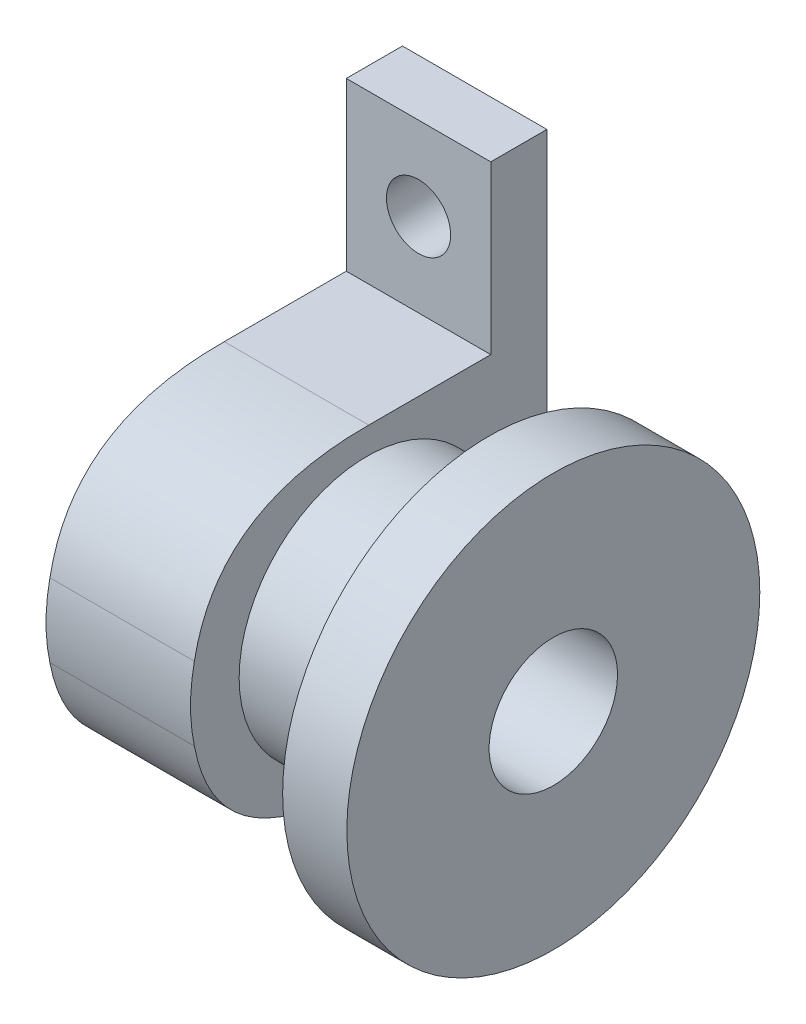
SolidWorks part; units mm, degrees
ref_plane "Front Plane" through (0, 0, 0) normal (1, 0, 0) x (0, 1, 0)
ref_plane "Top Plane" through (0, 0, 0) normal (0, 0, 1) x (0, 1, 0)
ref_plane "Right Plane" through (0, 0, 0) normal (0, 1, 0) x (-1, 0, 0)
sketch "Sketch1" plane through (0, 0, 0) normal (0, 0, 1) x (0, 1, 0)
  line L0 (-50, 0) -> (50, 0)
  line L1 (-50, 0) -> (-50, -22.5)
  line L2 (-50, -22.5) -> (50, -22.5)
  line L3 (50, -22.5) -> (50, 0)
  point P4 (0, 0)
  dimension "D1" = 100
  dimension "D2" = 22.5
extrude "Boss-Extrude1" add sketch "Sketch1" along normal blind 55.5
sketch "Sketch2" plane through (22.5, 0, 0) normal (1, 0, 0) x (0, 1, 0)
  line L0 (0, 0) -> (0, 0.5)
  line L1 (-24, 0) -> (-24, 55.5)
  line L2 (-50, 0) -> (50, 0) construction
  line L4 (-50, 55.5) -> (-50, 0) construction
  line L5 (50, 55.5) -> (50, 0) construction
  line L6 (19.6311, 8.742) -> (50, 8.742)
  line L8 (50, 55.5) -> (50, 14.5743)
  line L10 (-50, 55.5) -> (50, 55.5) construction
  line L12 (24, 0) -> (24, 55.5)
  line L13 (0, 0.5) -> (0, 55.5)
  line L14 (-24, 8.742) -> (-19.6311, 8.742)
  line L15 (-24, 8.742) -> (-50, 8.742)
  circle A4 centre (0, 28) radius 27.5
  circle A5 centre (0, 28) radius 10
  spline S0 degree 2 poles (0, 55.5) (-24.2004, 54.7772) (-24, 27.75) knots 0 0 0 1 1 1
  spline S1 degree 2 poles (0, 55.5) (24.2004, 54.7772) (24, 27.75) knots 0 0 0 1 1 1
  line M7 (50, 0) -> (50, 55.5)
  line M8 (50, 55.5) -> (-50, 55.5)
  line M9 (-50, 55.5) -> (-50, 0)
  dimension "D2" = 20
  dimension "D1" = 0.5
extrude "Cut-Extrude1" cut sketch "Sketch2" against normal through all contours A4 L1 L15 M8 M9 | S0 L1 A4 | S0 A4 L1 | S0 A4 L1 M8 | L13 A5 | L13 A5 | A4 S1 L12 M8 | A4 L12 L6 M7 M8 | L12 S1 A4 | A4 S1 L12
sketch "Sketch3" plane through (0, 0, 8.742) normal (0, 0, 1) x (1, 0, 0)
  line L0 (22.5, 50) -> (0, 24)
  circle A0 centre (11.25, 37) radius 5
  dimension "D1" = 10
extrude "Cut-Extrude2" cut sketch "Sketch3" against normal through all contours L0 A0 | L0 A0
sketch "Sketch5" plane through (0, 0, 8.742) normal (0, 0, 1) x (1, 0, 0)
  line L0 (0, -24) -> (22.5, -50)
  circle A0 centre (11.25, -37) radius 4.9984
extrude "Cut-Extrude3" cut sketch "Sketch5" against normal through all contours L0 A0 | L0 A0
sketch "Sketch6" plane through (0, 0, 0) normal (-1, 0, 0) x (0, -1, 0)
  circle A0 centre (0, 28) radius 12
  circle M1 centre (0, 28) radius 10
  dimension "D1" = 24
extrude "Boss-Extrude2" add sketch "Sketch6" along normal blind 5 contours A0 M1
sketch "Sketch7" plane through (22.5, 0, 0) normal (1, 0, 0) x (0, 1, 0)
  circle A1 centre (0, 28) radius 19.9274
extrude "Boss-Extrude3" add sketch "Sketch7" along normal blind 19
sketch "Sketch9" plane through (41.5, 0, 0) normal (1, 0, 0) x (0, 1, 0)
  circle A0 centre (0, 28) radius 32.1557
  circle A1 centre (0, 28) radius 10
extrude "Boss-Extrude5" add sketch "Sketch9" along normal blind 10
split "Split1" [suppressed] bodies to split 105
